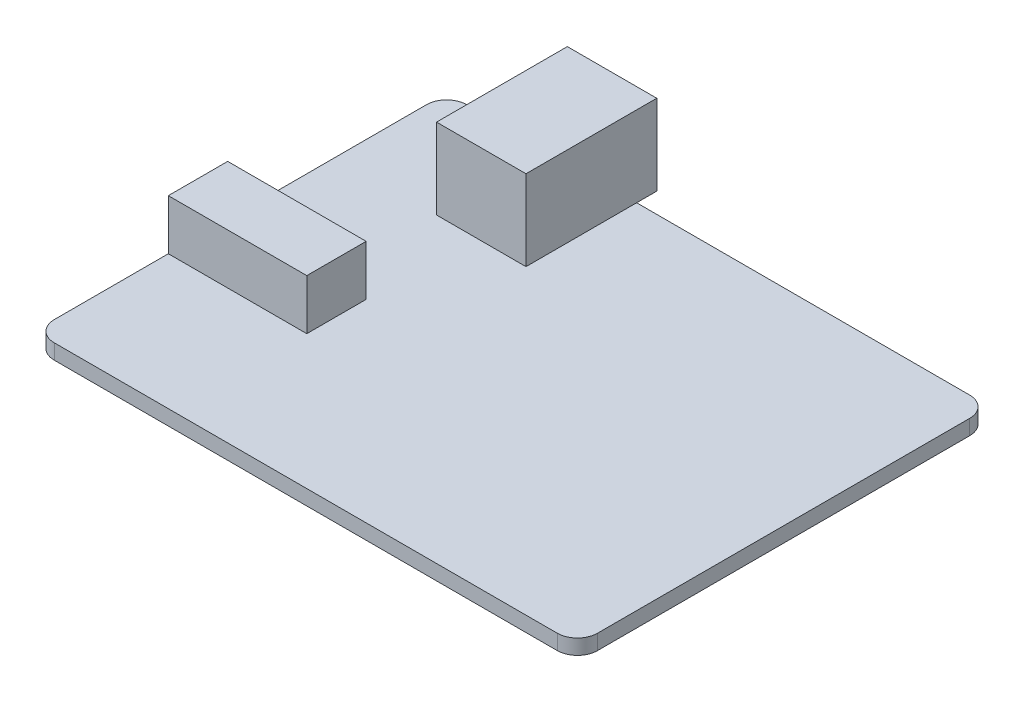
SolidWorks part; units mm, degrees
ref_plane "Front Plane" through (0, 0, 0) normal (0, 0, 1) x (1, 0, 0)
ref_plane "Top Plane" through (0, 0, 0) normal (0, 1, 0) x (1, 0, 0)
ref_plane "Right Plane" through (0, 0, 0) normal (1, 0, 0) x (0, 0, -1)
sketch "Sketch1" plane through (0, 0, 0) normal (0, 1, 0) x (1, 0, 0)
  line L1 (0, 0) -> (54, 0)
  line L2 (0, 0) -> (0, 41)
  line L3 (0, 41) -> (54, 41)
  line L4 (54, 0) -> (54, 41)
  dimension "D1" = 54
  dimension "D2" = 41
extrude "Boss-Extrude1" add sketch "Sketch1" along normal blind 1.5
sketch "Sketch2" plane through (0, 1.5, 0) normal (0, 1, 0) x (1, 0, 0)
  line L0 (0, 41) -> (0, 0) construction
  line L1 (10, 30) -> (18.89, 30)
  line L2 (10, 30) -> (10, 43)
  line L3 (10, 43) -> (18.89, 43)
  line L4 (18.89, 30) -> (18.89, 43)
  line L5 (54, 41) -> (0, 41) construction
  dimension "D1" = 8.89
  dimension "D2" = 10
  dimension "D3" = 2
  dimension "D4" = 13
extrude "Boss-Extrude2" add sketch "Sketch2" along normal blind 8
fillet "Fillet1" radius 2 4 edges at (0, 0.75, 0) (54, 0.75, 0) (54, 0.75, -41) (0, 0.75, -41)
sketch "Sketch3" plane through (0, 1.5, 0) normal (0, 1, 0) x (1, 0, 0)
  line L0 (0, 39) -> (0, 2) construction
  line L1 (13.765, 19.2369) -> (0, 19.2369)
  line L2 (13.765, 19.2369) -> (13.765, 13.3356)
  line L3 (13.765, 13.3356) -> (0, 13.3356)
  line L4 (0, 19.2369) -> (0, 13.3356)
extrude "Boss-Extrude3" add sketch "Sketch3" along normal blind 5
sketch "Sketch4" plane through (0, 0, 0) normal (-1, 0, 0) x (0, 0, 1)
  line L0 (-19.2369, 6.5) -> (-13.3356, 1.5) construction
  circle A0 centre (-16.2862, 4) radius 1.5875
  dimension "D1" = 3.175
extrude "Cut-Extrude1" cut sketch "Sketch4" against normal blind 10
